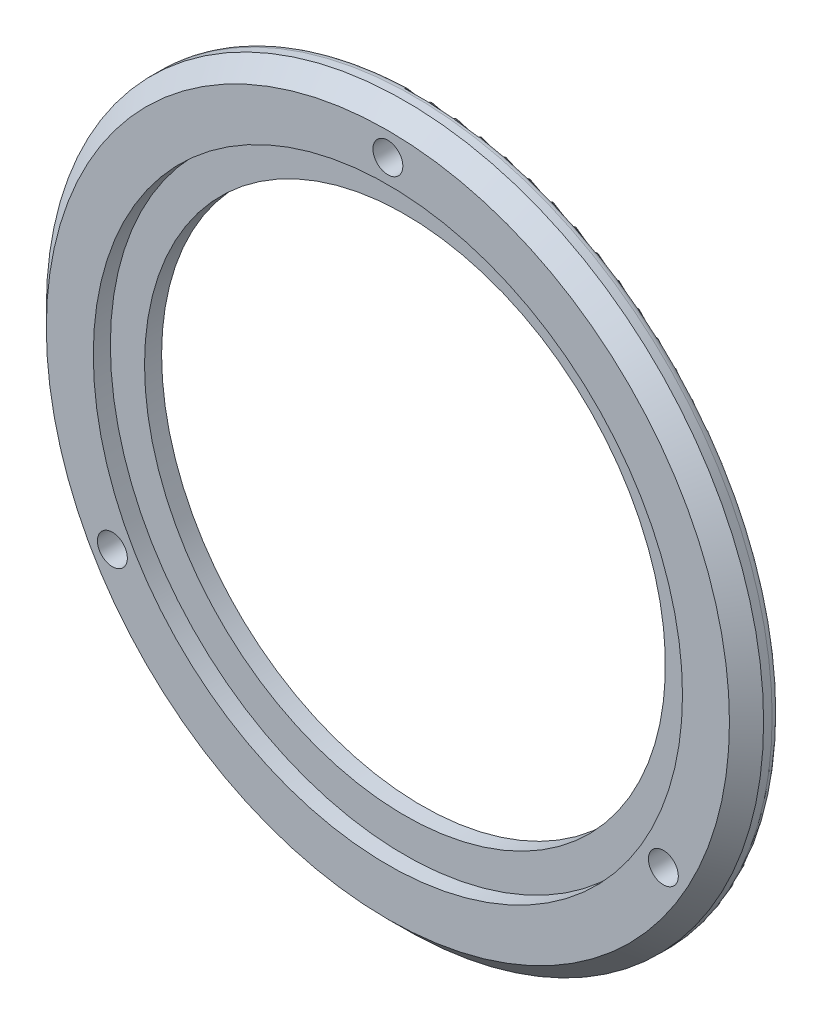
SolidWorks part; units mm, degrees
ref_plane "Спереди" through (0, 0, 0) normal (0, 0, 1) x (1, 0, 0)
ref_plane "Сверху" through (0, 0, 0) normal (0, 1, 0) x (1, 0, 0)
ref_plane "Справа" through (0, 0, 0) normal (1, 0, 0) x (0, 0, -1)
sketch "Эскиз1" plane through (0, 0, 0) normal (0, 0, 1) x (1, 0, 0)
  circle A0 centre (0, 0) radius 42
  circle A1 centre (0, 0) radius 30.5
  dimension "D1" = 61
  dimension "D2" = 84
extrude "Бобышка-Вытянуть1" add sketch "Эскиз1" along normal blind 4
chamfer "Фаска1" distance 2 angle 45 1 edges at (42, 0, 4)
sketch "Эскиз3" plane through (0, 0, 4) normal (0, 0, 1) x (1, 0, 0)
  circle A0 centre (0, 0) radius 34.5
  dimension "D1" = 69
extrude "Вырез-Вытянуть2" cut sketch "Эскиз3" against normal blind 2 contours A0
sketch "Эскиз4" plane through (0, 0, 4) normal (0, 0, 1) x (1, 0, 0)
  circle A0 centre (0, 37.25) radius 1.75
  circle A2 centre (0, 0) radius 30.5 construction
  circle A3 centre (32.2594, -18.625) radius 1.75
  circle A4 centre (-32.2594, -18.625) radius 1.75
  circle A5 centre (0, 0) radius 34.5 construction
  circle A9 centre (0, 0) radius 42 construction
  point P13 (0, 0)
  dimension "D2" = 3.5
  dimension "D3" = 1
  dimension "D1" = 3
extrude "Вырез-Вытянуть5" cut sketch "Эскиз4" against normal through all contours A4 | A3 | A0
fillet "Скругление2" radius 1 1 edges at (42, 0, 0)
